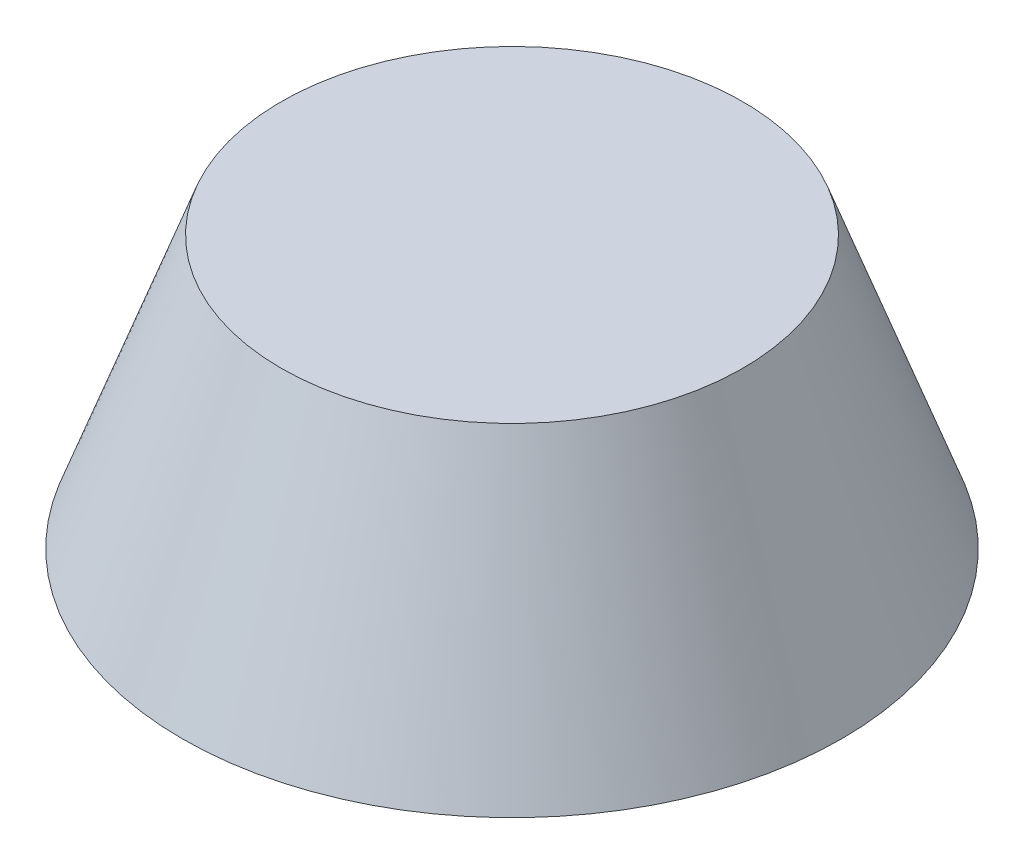
SolidWorks part; units mm, degrees
ref_plane "前视基准面" through (0, 0, 0) normal (0, 0, 1) x (1, 0, 0)
ref_plane "上视基准面" through (0, 0, 0) normal (0, 1, 0) x (1, 0, 0)
ref_plane "右视基准面" through (0, 0, 0) normal (1, 0, 0) x (0, 0, -1)
other "Configuration Table"
sketch "草图1" plane through (0, 0, 0) normal (0, 1, 0) x (1, 0, 0)
  circle A0 centre (0, 0) radius 17
extrude "凸台-拉伸1" add sketch "草图1" along normal blind 14 draft 20
